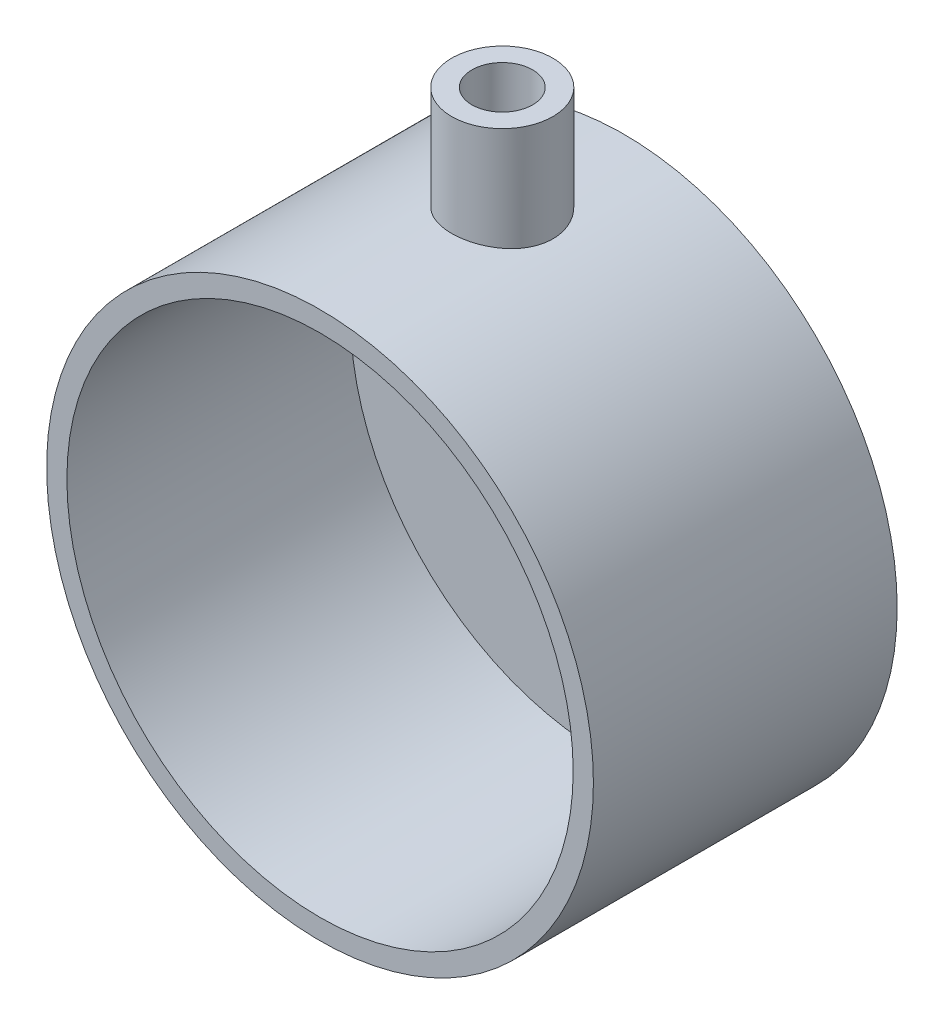
SolidWorks part; units mm, degrees
ref_plane "前视基准面" through (0, 0, 0) normal (0, 0, 1) x (1, 0, 0)
ref_plane "上视基准面" through (0, 0, 0) normal (0, 1, 0) x (1, 0, 0)
ref_plane "右视基准面" through (0, 0, 0) normal (1, 0, 0) x (0, 0, -1)
sketch "草图1" plane through (0, 0, 0) normal (0, 0, 1) x (1, 0, 0)
  circle A0 centre (0, 0) radius 27
  circle A1 centre (0, 0) radius 25
  point P3 (0, 0)
  dimension "D1" = 54
  dimension "D2" = 2
extrude "凸台-拉伸1" add sketch "草图1" along normal blind 2 contours A0
sketch "草图2" plane through (0, 0, 0) normal (0, 0, 1) x (1, 0, 0)
  circle A1 centre (0, 0) radius 27
  circle A2 centre (0, 0) radius 25
  circle A3 centre (0, 0) radius 25
  dimension "D1" = 2
  dimension "D2" = 2
extrude "凸台-拉伸2" add sketch "草图2" along normal blind 30
sketch "草图3" plane through (0, 0, 0) normal (0, 0, 1) x (1, 0, 0)
  circle A0 centre (0, 0) radius 2.5
extrude "切除-拉伸1" cut sketch "草图3" against normal mid plane 30
ref_plane "基准面1" through (0, 27, 0) normal (0, 1, 0) x (1, 0, 0)
sketch "草图4" plane through (0, 27, 0) normal (0, 1, 0) x (1, 0, 0)
  line L0 (0, 0) -> (0, -12) construction
  circle A0 centre (0, -12) radius 5
  dimension "D2" = 10
  dimension "D1" = 12
extrude "凸台-拉伸3" add sketch "草图4" along normal blind 10 and the other way blind 2
sketch "草图5" plane through (0, 37, 0) normal (0, 1, 0) x (1, 0, 0)
  circle A0 centre (0, -12) radius 3
extrude "切除-拉伸2" cut sketch "草图5" against normal blind 50
